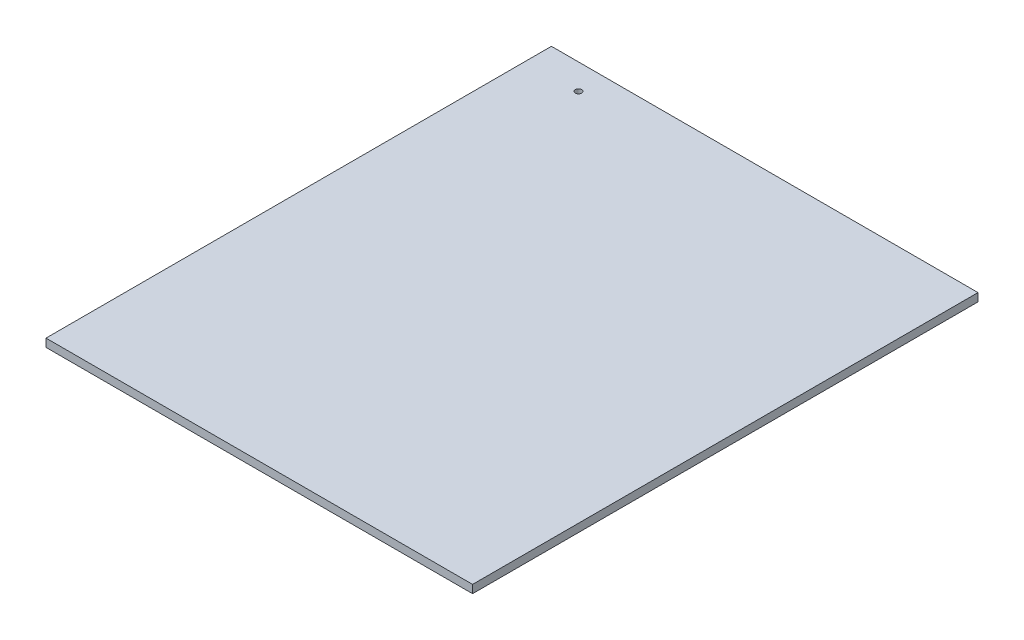
SolidWorks part; units mm, degrees
ref_plane "Front Plane" through (0, 0, 0) normal (0, 0, 1) x (1, 0, 0)
ref_plane "Top Plane" through (0, 0, 0) normal (0, 1, 0) x (1, 0, 0)
ref_plane "Right Plane" through (0, 0, 0) normal (1, 0, 0) x (0, 0, -1)
sketch "Sketch1" plane through (0, 0, 0) normal (0, 1, 0) x (1, 0, 0)
  line L0 (-24.6732, 20.6415) -> (-24.6732, -229.3585) construction
  line L6 (-130.1732, 20.6415) -> (80.8268, 20.6415)
  line L7 (-130.1732, 20.6415) -> (-130.1732, -229.3585)
  line L16 (-130.1732, -229.3585) -> (80.8268, -229.3585)
  line L21 (80.8268, 20.6415) -> (80.8268, -229.3585)
  line L38 (-130.1732, -104.3585) -> (80.8268, -104.3585) construction
  circle A15 centre (-104.1732, 8.0313) radius 1.55
  dimension "D3" = 3.1
  dimension "D1" = 250
  dimension "D2" = 211
  dimension "D4" = 26
extrude "Boss-Extrude1" add sketch "Sketch1" along normal blind 4
equation "\"cf_tube_outer_diameter\"= 25mm"
equation "\"cf_tube_inner_diameter\" = 21mm"
equation "\"mid_plate_mid_to_top\" = 100mm"
equation "\"mid_plate_mid_to_bottom\" = 30mm"
equation "\"mid_plate_horizontal_spacing\"=250mm"
equation "\"cf_plate_thickness\" =4mm"
equation "\"mid_tube_length\" = 500mm"
equation "\"mid_plate_bottom_width\" = 180mm"
equation "\"mid_support_plate_distance\" = 250mm"
equation "\"nut_strip_2_hole_distance\" = 7mm"
equation "\"nut_strip_hole_diameter\" = 2.5mm"
equation "\"nut_strip_hole_to_edge_distance\"= 2.5mm"
equation "\"D1@Sketch1\"=\"mid_plate_horizontal_spacing\""
equation "\"D1@Boss-Extrude1\"=\"cf_plate_thickness\""
